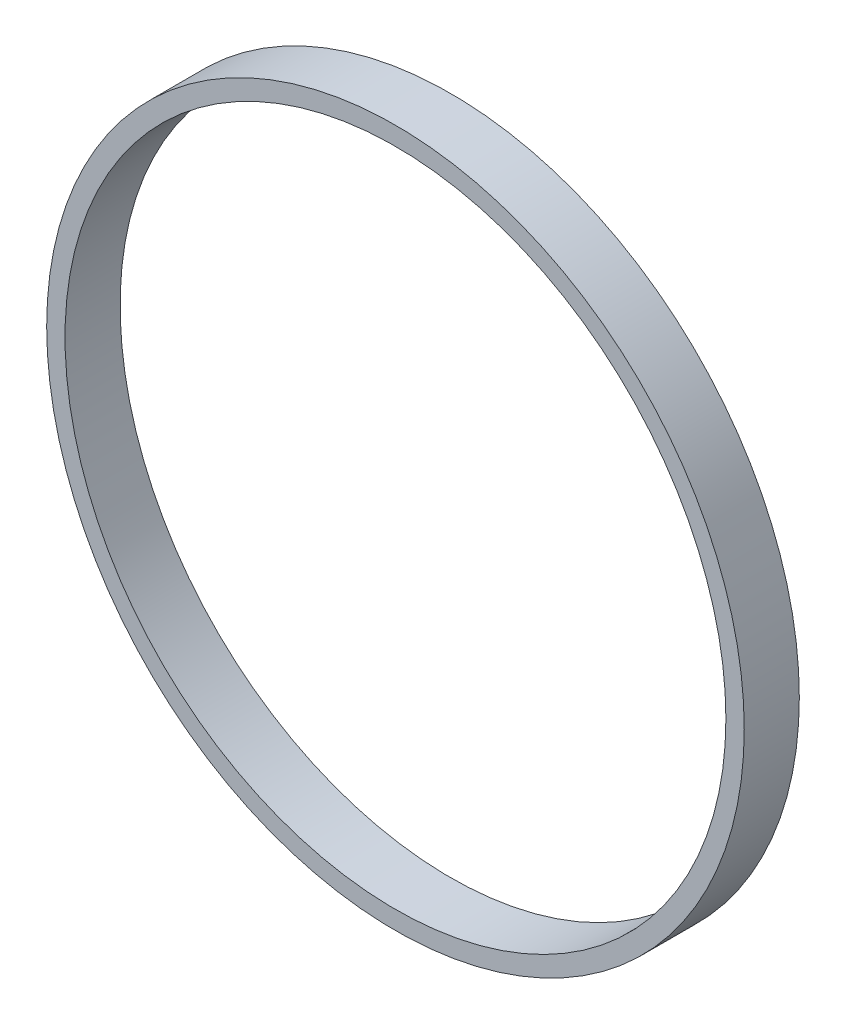
SolidWorks part; units mm, degrees
material "PC 高粘度"
ref_plane "前视基准面" through (0, 0, 0) normal (0, 0, 1) x (1, 0, 0)
ref_plane "上视基准面" through (0, 0, 0) normal (0, 1, 0) x (1, 0, 0)
ref_plane "右视基准面" through (0, 0, 0) normal (1, 0, 0) x (0, 0, -1)
sketch "草图1" plane through (0, 0, 0) normal (0, 0, 1) x (1, 0, 0)
  circle A0 centre (0, 0) radius 4.75
extrude "凸台-拉伸1" add sketch "草图1" along normal blind 0.75
sketch "草图3" plane through (0, 0, 0.75) normal (0, 0, 1) x (1, 0, 0)
  circle A0 centre (0, 0) radius 4.5
extrude "切除-拉伸1" cut sketch "草图3" against normal blind 0.75
